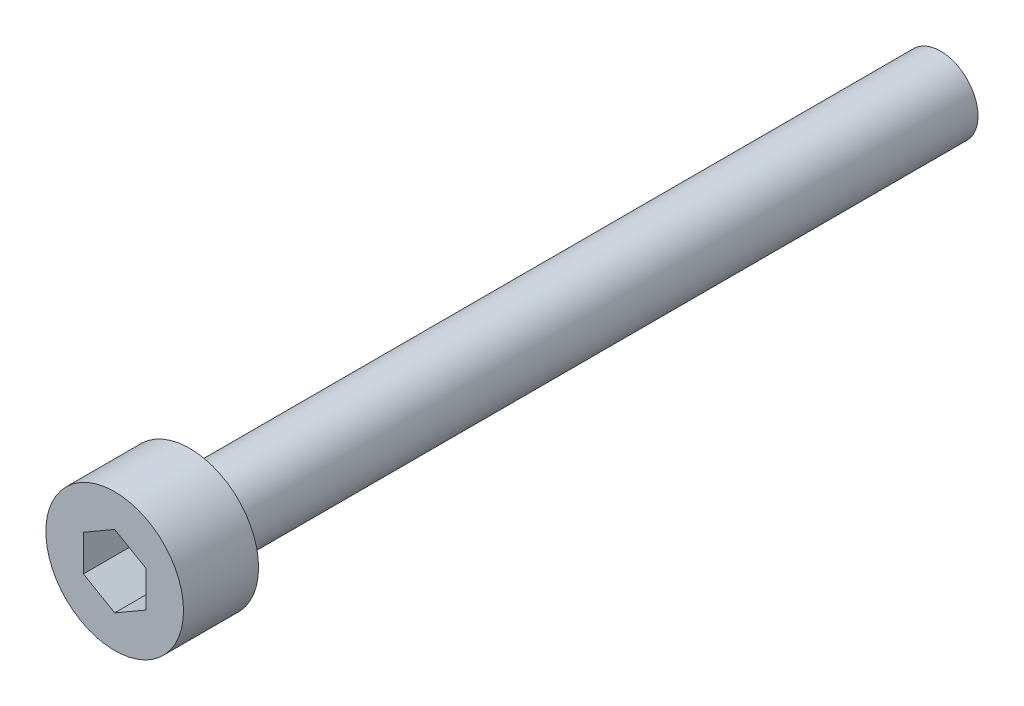
SolidWorks part; units mm, degrees
ref_plane "前视基准面" through (0, 0, 0) normal (0, 0, 1) x (1, 0, 0)
ref_plane "上视基准面" through (0, 0, 0) normal (0, 1, 0) x (1, 0, 0)
ref_plane "右视基准面" through (0, 0, 0) normal (1, 0, 0) x (0, 0, -1)
other "Configuration Table"
sketch "Profile_1" plane through (0, 0, 0) normal (0, 0, 1) x (1, 0, 0)
  circle A0 centre (0, 0) radius 1.5
extrude "Thread_envelope" add sketch "Profile_1" along normal blind 30 from offset 30
sketch "Profile_2" plane through (0, 0, 0) normal (0, 0, 1) x (1, 0, 0)
  line L0 (1.25, 0.7217) -> (0, 1.4434)
  line L1 (0, 1.4434) -> (-1.25, 0.7217)
  line L2 (-1.25, 0.7217) -> (-1.25, -0.7217)
  line L3 (-1.25, -0.7217) -> (0, -1.4434)
  line L4 (0, -1.4434) -> (1.25, -0.7217)
  line L5 (1.25, -0.7217) -> (1.25, 0.7217)
  circle A0 centre (0, 0) radius 2.75
extrude "Socket_head" add sketch "Profile_2" along normal blind 3 from offset 0
